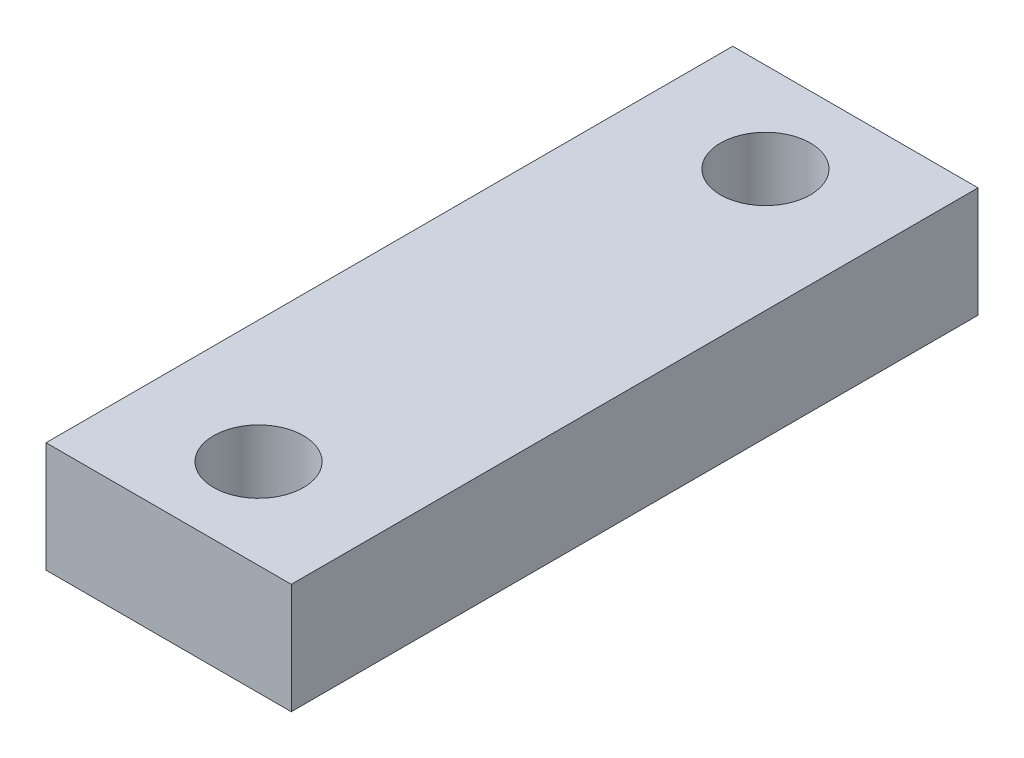
SolidWorks part; units mm, degrees
ref_plane "Front Plane" through (0, 0, 0) normal (0, 0, 1) x (1, 0, 0)
ref_plane "Top Plane" through (0, 0, 0) normal (0, 1, 0) x (1, 0, 0)
ref_plane "Right Plane" through (0, 0, 0) normal (1, 0, 0) x (0, 0, -1)
sketch "Sketch1" plane through (0, 0, 0) normal (1, 0, 0) x (0, 0, -1)
  line L0 (0, 0) -> (42, 0)
  line L1 (42, 0) -> (42, 6.75)
  line L6 (42, 6.75) -> (0, 6.75)
  line L7 (0, 6.75) -> (0, 0)
  dimension "D2" = 42
  dimension "D4" = 6.75
extrude "ProfileBoss-Extrude1" add sketch "Sketch1" along normal blind 15
sketch "Sketch2" plane through (0, 6.75, 0) normal (0, 1, 0) x (1, 0, 0)
  line L0 (15, 0) -> (0, 0) construction
  line L2 (0, 42) -> (0, 0) construction
  line L3 (15, 42) -> (0, 42) construction
  circle A0 centre (7.5, 5.5) radius 2.75
  circle A1 centre (7.5, 36.5) radius 2.75
  dimension "D1" = 5.5
  dimension "D2" = 5.5
  dimension "D4" = 7.5
  dimension "D5" = 31
  dimension "D3" = 5.5
extrude "MountHolesCut-Extrude1" cut sketch "Sketch2" against normal through all
equation "\"SK8RodShaftSupportHeight\"= 42mm"
equation "\"SK8RodShaftSupportLength\"= 15mm"
equation "\"SK8MountHoldeDiameter\"= 5mm"
equation "\"SK8RiserWidth\"= 6.75mm'Measured to meet Nema17 Mount Hole Center axis"
equation "\"D2@Sketch2\"=\"SK8MountHoleFromEitherEnd\""
equation "\"D1@Sketch2\"= \"SK8MountHoldeDiameter\" + .5mm'Add .5mm to allow easier install"
equation "\"D4@Sketch1\"=\"SK8RiserWidth\""
equation "\"D2@Sketch1\"=\"SK8RodShaftSupportHeight\""
equation "\"SK8MountHoleFromSide\"= \"SK8RodShaftSupportLength\" / 2"
equation "\"D4@Sketch2\"=\"SK8MountHoleFromSide\""
equation "\"SK8MountHoleFromEitherEnd\"= 5.5mm"
equation "\"D3@Sketch2\"=\"SK8MountHoleFromEitherEnd\""
